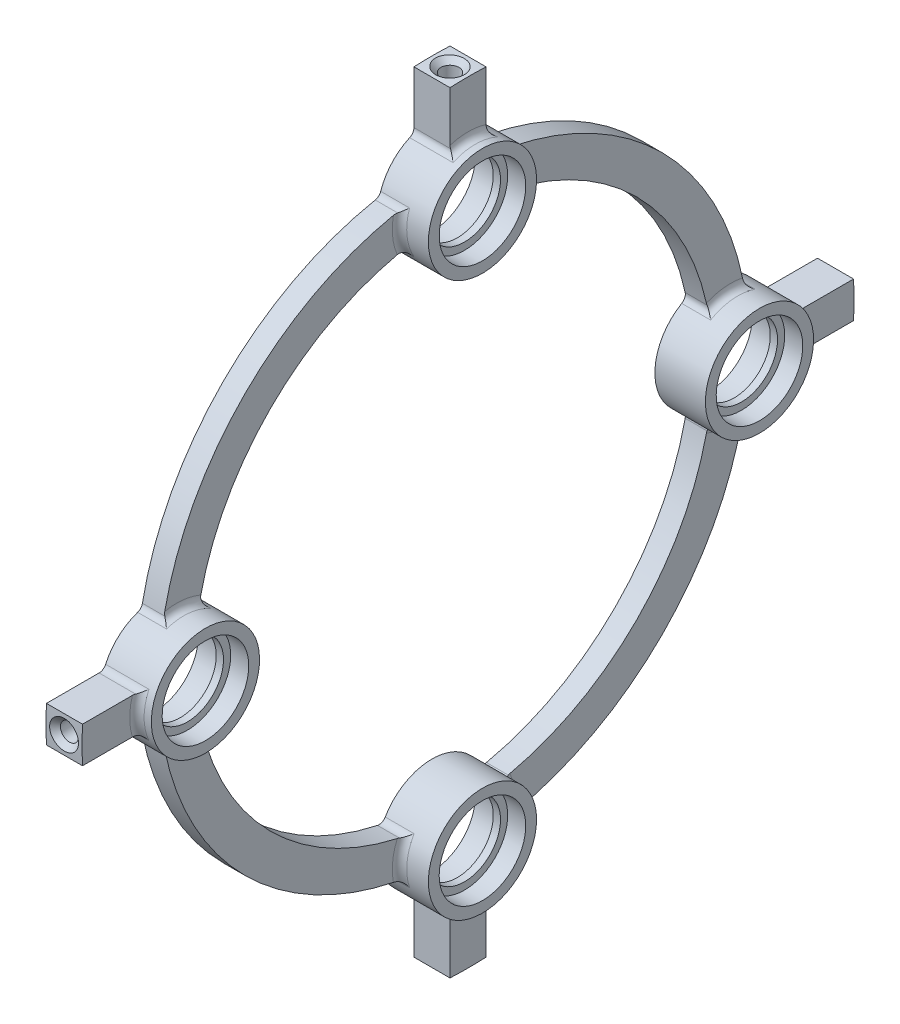
SolidWorks part; units mm, degrees
material "ABS"
ref_plane "Спереди" through (0, 0, 0) normal (0, 0, 1) x (1, 0, 0)
ref_plane "Сверху" through (0, 0, 0) normal (0, 1, 0) x (1, 0, 0)
ref_plane "Справа" through (0, 0, 0) normal (1, 0, 0) x (0, 0, -1)
sketch "Эскиз3" plane through (0, 0, 0) normal (1, 0, 0) x (0, 0, -1)
  circle A0 centre (0, 0) radius 38.4 construction
  dimension "D1" = 76.8
sketch "Эскиз1" plane through (0, 0, 0) normal (1, 0, 0) x (0, 0, -1)
  line L0 (40.9, 0) -> (35.9, 0) construction
  circle A3 centre (0, 0) radius 40.9
  circle A4 centre (0, 0) radius 35.9
  circle A5 centre (0, 0) radius 38.4 construction
  point P9 (38.4, 0)
  dimension "D1" = 5
extrude "Бобышка-Вытянуть1" add sketch "Эскиз1" along normal blind 3
sketch "Эскиз2" plane through (0, 0, 0) normal (-1, 0, 0) x (0, 0, 1)
  circle A0 centre (0, 38.4) radius 7.5
  circle A1 centre (0, 0) radius 38.4 construction
  dimension "D1" = 15
extrude "Бобышка-Вытянуть2" add sketch "Эскиз2" against normal blind 7
sketch "Эскиз4" plane through (0, 0, 0) normal (-1, 0, 0) x (0, 0, 1)
  circle A0 centre (0, 38.4) radius 5
  dimension "D1" = 10
extrude "Вырез-Вытянуть1" cut sketch "Эскиз4" against normal through all
sketch "Эскиз5" plane through (0, 0, 0) normal (-1, 0, 0) x (0, 0, 1)
  circle A0 centre (0, 38.4) radius 6
  dimension "D1" = 12
extrude "Вырез-Вытянуть2" cut sketch "Эскиз5" against normal blind 3.5
sketch "Эскиз6" plane through (7, 0, 0) normal (1, 0, 0) x (0, 0, -1)
  circle A0 centre (0, 38.4) radius 6
  dimension "D1" = 12
extrude "Вырез-Вытянуть3" cut sketch "Эскиз6" against normal blind 2.5
sketch "Эскиз7" plane through (0, 0, 0) normal (-1, 0, 0) x (0, 0, 1)
  line L0 (0, 0) -> (0, 53.5) construction
  line L1 (-2.5, 53.4416) -> (-2.5, 45.4711)
  line L2 (2.5, 53.4416) -> (2.5, 45.4711)
  circle A0 centre (0, 0) radius 53.5 construction
  arc A1 (7.2685, 40.249) -> (-7.2685, 40.249) centre (0, 38.4) ccw construction
  arc A2 (-2.5, 53.4416) -> (2.5, 53.4416) centre (0, 0) cw
  arc A3 (-2.5, 45.4711) -> (2.5, 45.4711) centre (0, 38.4) cw
  dimension "D1" = 107
  dimension "D2" = 5
extrude "Бобышка-Вытянуть3" add sketch "Эскиз7" against normal blind 5
fillet "Скругление1" radius 1 9 edges at (3, 37.7091, 7.4681) (3, 37.7091, -7.4681) (1.5, 35.249, 6.8059) (1.5, 35.249, -6.8059) (1.5, 40.249, -7.2685) (1.5, 40.249, 7.2685) (5, 45.9, 0) (2.5, 45.4711, 2.5) (2.5, 45.4711, -2.5)
hole_wizard "Отверстие обработанное метчиком M31" positions "Трехмерный эскиз1" profile "Эскиз8" tap size "M3" standard "ISO"
sketch3d "Трехмерный эскиз1"
  line L2 (2.5, 53.4416, 2.5) -> (2.5, 53.4416, 0) construction
  line L3 (5, 53.4416, 2.5) -> (0, 53.4416, 2.5) construction
  line L7 (2.5, 53.4416, 0) -> (2.5, 53.5, 0) construction
  line L12 (0, 53.4416, 2.5) -> (0, 53.4416, -2.5) construction
  line L13 (2.5, 53.4416, 0) -> (0, 53.4416, 0) construction
  point P0 (2.5, 53.5, 0)
  point P50 (0, 53.4416, 0)
sketch "Эскиз8" plane through (2.5, 53.5, 0) normal (1, 0, 0) x (0, 0, 1)
  line L0 (0, 0) -> (0, 7.7511)
  line L1 (0, 7.7511) -> (1.25, 7)
  line L2 (1.25, 7) -> (1.25, 0.75)
  line L3 (1.25, 0.75) -> (2, 0)
  line L5 (2, 0) -> (0, 0)
  line L6 (-1.25, 0.75) -> (-2, 0) construction
  line L10 (0, 7.7511) -> (-1.25, 7) construction
  line L11 (0, -6.35) -> (0, 107.95) construction
  dimension "Диаметр сверла" = 2.5
  dimension "Глубина сверла" = 7
  dimension "Диаметр передней зенковки" = 4
  dimension "Угол передней зенковки" = 90
  dimension "Угол заточки сверла" = 118
cosmetic thread "Отверстие резьбы1" parameters "D1"=6, "D2"=3
pattern_circular "Круговой массив1" count 4 over 360 about axis through (0, 0, 0) along (1, 0, 0) of "Бобышка-Вытянуть2", "Вырез-Вытянуть1", "Вырез-Вытянуть2", "Вырез-Вытянуть3", "Бобышка-Вытянуть3", "Скругление1", "Отверстие обработанное метчиком M31"
